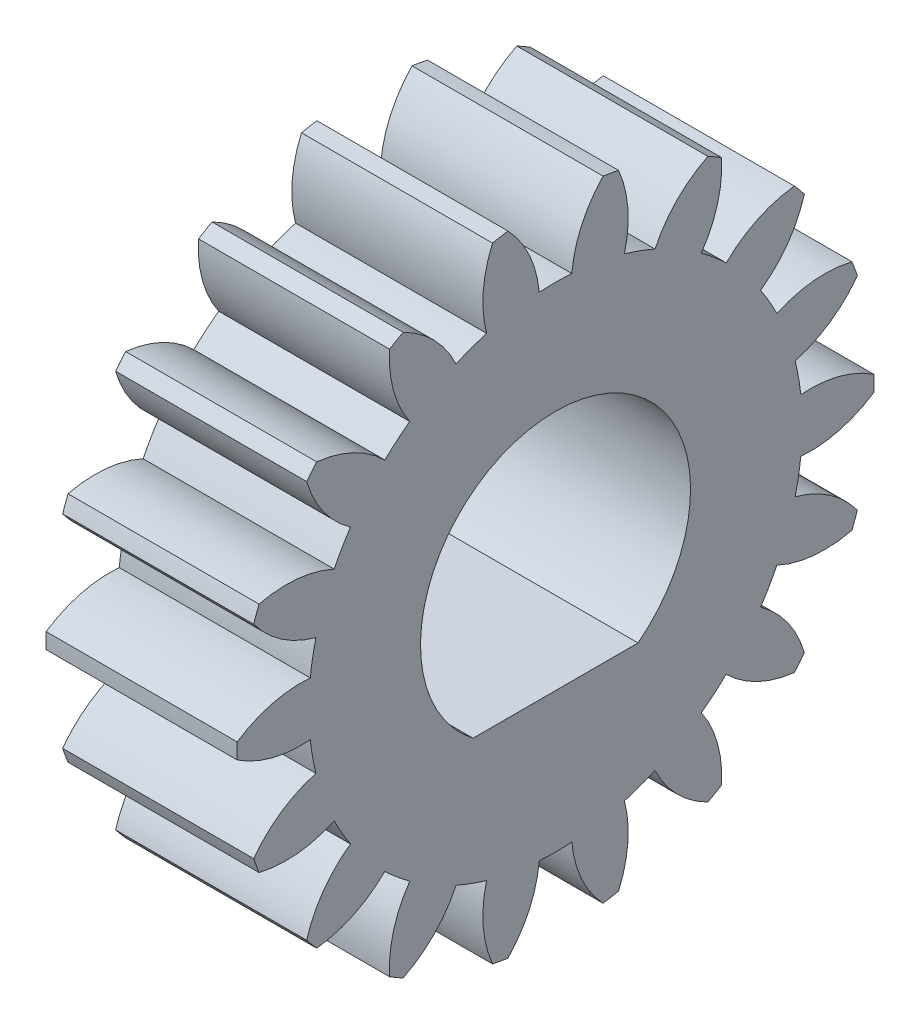
SolidWorks part; units mm, degrees
ref_plane "Plane1" through (0, 0, 0) normal (0, 0, 1) x (1, 0, 0)
ref_plane "Plane2" through (0, 0, 0) normal (0, 1, 0) x (1, 0, 0)
ref_plane "Plane3" through (0, 0, 0) normal (1, 0, 0) x (0, 0, -1)
sketch "HoldingSke" plane through (0, 0, 0) normal (0, 1, 0) x (1, 0, 0)
  line L0 (0, 0) -> (1.9021, -0.618)
  line L1 (-15, 0) -> (100, 0) construction
  line L2 (0, 0) -> (-2.1039, 2.3779)
  line L3 (0, 0) -> (-11.863, 4.5341)
  line L4 (0, 0) -> (8.2133, 2.6687)
  line L5 (0, 0) -> (-46.8476, -17.4728)
  line L6 (0, 0) -> (-3.3159, -2.2372)
  line L7 (-2.1039, 2.3779) -> (8.6586, 51.2059)
  line L8 (-76.2, 54.61) -> (-76.1, 54.61)
  line L9 (-71.009, 38.7566) -> (-53.1078, 45.2721)
  line L10 (-76.2, 71.12) -> (104.1128, 71.12)
  line L11 (0, 0) -> (-4, 0)
  line L12 (-76.2, 101.6) -> (-76.181, 101.6)
  line L13 (24.9733, 27.94) -> (52.9518, 28.4284)
  line L14 (24.9733, 27.94) -> (24.9743, 27.94)
  line L15 (24.9733, 27.94) -> (100.4006, 29.5858)
  line L16 (-63.627, -0.5) -> (-12.827, -0.5)
  circle A0 centre (0, 0) radius 0.5
  circle A1 centre (0, 0) radius 3.874
  circle A2 centre (0, 0) radius 37.5
  circle A3 centre (0, 0) radius 0.5
  dimension "MHD" = 7.748
  dimension "Hub_dia" = 75
  dimension "Bore" = 1
  dimension "MBD" = 1
  dimension "Num_teeth" = 18
  dimension "Pitch" = 2
  dimension "Overall_len" = 50
  dimension "Show_teeth" = 18
  dimension "Thickness" = 4
  dimension "OAL" = 50.0001
  dimension "T_dim" = 0.1
  dimension "Ap" = 20
  dimension "H" = 19.05
  dimension "Pitch_radius" = 180.3128
  dimension "Width" = 4
  dimension "Backlash" = 0.019
  dimension "Addendum_fac" = 1
  dimension "Dedendum_fac" = 1.25
  dimension "Clearance_fac" = 0.25
  dimension "Dedendum_add" = 0.001
  dimension "Module" = 0.5
sketch "BasProSke" plane through (0, 0, 0) normal (0, 1, 0) x (1, 0, 0)
  line L0 (-10, 0) -> (60, 0) construction
  line L1 (0, 0) -> (0, 5)
  line L2 (0, 0) -> (4, 0)
  line L3 (4, 0) -> (4, 5)
  line L4 (4, 5) -> (0, 5)
  dimension "Thickness" = 4
  dimension "Diameter" = 10
revolve "Base-Revolve" add sketch "BasProSke" angle 360 about L0
sketch "TooCutSke" plane through (0, 0, 0) normal (1, 0, 0) x (0, 0, -1)
  line L1 (0, 0) -> (0, 107) construction
  line L2 (0, 0) -> (-0.4254, 4.4798) construction
  line L3 (0, 0) -> (-1.5579, 8.835) construction
  line L4 (-0.4254, 4.4798) -> (-0.7789, 4.4175) construction
  arc A0 (0.2553, 3.8656) -> (-0.2553, 3.8656) centre (0, 0) ccw
  arc A1 (0.7686, 4.9663) -> (-0.7686, 4.9663) centre (0, 0) ccw
  circle A2 centre (0, 0) radius 4.5 construction
  circle A3 centre (0, 0) radius 4.2286 construction
  arc A4 (-0.2553, 3.8656) -> (-0.7686, 4.9663) centre (-2.0476, 3.6998) ccw
  arc A5 (0.7686, 4.9663) -> (0.2553, 3.8656) centre (2.0476, 3.6998) ccw
  dimension "Root_dia" = 7.748
  dimension "Overcut_dia" = 10.0508
  dimension "Pitch_dia" = 9
  dimension "Base_dia" = 8.4572
  dimension "Flank_rad" = 1.8
  dimension "Half_ang" = 10
  dimension "Half_CT" = 0.359
extrude "ToothCut" cut sketch "TooCutSke" along normal through all
fillet "Breaks" [suppressed] radius 0.01
fillet "RootFillets" [suppressed] radius 0.126
pattern_circular "TeethCuts" count 18 every 20 about axis through (-10, 0, 0) along (1, 0, 0) of "ToothCut", "RootFillets", "Breaks"
sketch "HubNeaOneSke" plane through (0, 0, 0) normal (-1, 0, 0) x (0, 0, 1)
  circle A0 centre (0, 0) radius 3.874
  dimension "Diameter" = 7.748
extrude "HubNearOne" [suppressed] add sketch "HubNeaOneSke" along normal blind 46.0001
sketch "HubNeaBotSke" plane through (0, 0, 0) normal (-1, 0, 0) x (0, 0, 1)
  circle A0 centre (0, 0) radius 3.874
  dimension "Diameter" = 7.748
extrude "HubNearBoth" [suppressed] add sketch "HubNeaBotSke" along normal blind 23
ref_plane "FarPln" through (4, 0, 0) normal (1, 0, 0) x (0, 0, -1)
sketch "HubFarSke" plane through (4, 0, 0) normal (1, 0, 0) x (0, 0, -1)
  circle A0 centre (0, 0) radius 3.874
  dimension "Diameter" = 7.748
extrude "HubFar" [suppressed] add sketch "HubFarSke" along normal blind 23
sketch "BorSke" plane through (0, 0, 0) normal (1, 0, 0) x (0, 0, -1)
  line L0 (-1.2954, -1.6782) -> (1.2954, -1.6782)
  line L2 (0, 0) -> (0, -1.6782)
  arc A0 (-1.2954, -1.6782) -> (1.2954, -1.6782) centre (0, 0) cw
extrude "Bore" cut sketch "BorSke" along normal mid plane 100.0001
sketch "KeySke" plane through (0, 0, 0) normal (1, 0, 0) x (0, 0, -1)
  line L0 (-0.05, 0) -> (-0.05, 0.6)
  line L1 (-0.05, 0.6) -> (0.05, 0.6)
  line L2 (0.05, 0.6) -> (0.05, 0)
  line L3 (0, 0) -> (0, 34) construction
  line L4 (-0.05, 0) -> (0.05, 0)
  dimension "Offset" = 0.6
  dimension "Width" = 0.1
extrude "Keyway" [suppressed] cut sketch "KeySke" along normal mid plane 100.0001
pattern_circular "Keyway2" [suppressed] count 2 every 90 about axis through (-10, 0, 0) along (1, 0, 0)
sketch "Sketch1" plane through (0, 0, 0) normal (-1, 0, 0) x (0, 0, 1)
  arc A72 (3.2201, 2.1539) -> (3.9082, 3.1187) centre (2.1803, 3.6232) ccw
  arc A73 (3.9082, 3.1187) -> (3.75, 3.3072) centre (0, 0) ccw
  arc A74 (3.75, 3.3072) -> (2.6803, 2.7971) centre (3.9467, 1.518) ccw
  arc A75 (2.6803, 2.7971) -> (2.2892, 3.1253) centre (0, 0) ccw
  arc A76 (2.2892, 3.1253) -> (2.6058, 4.2673) centre (0.8096, 4.1504) ccw
  arc A77 (2.6058, 4.2673) -> (2.3927, 4.3903) centre (0, 0) ccw
  arc A78 (2.3927, 4.3903) -> (1.562, 3.5451) centre (3.1895, 2.7763) ccw
  arc A79 (1.562, 3.5451) -> (1.0822, 3.7198) centre (0, 0) ccw
  arc A80 (1.0822, 3.7198) -> (0.9892, 4.9012) centre (-0.6587, 4.177) ccw
  arc A81 (0.9892, 4.9012) -> (0.7468, 4.9439) centre (0, 0) ccw
  arc A82 (0.7468, 4.9439) -> (0.2553, 3.8656) centre (2.0476, 3.6998) ccw
  arc A83 (0.2553, 3.8656) -> (-0.2553, 3.8656) centre (0, 0) ccw
  arc A84 (-0.2553, 3.8656) -> (-0.7468, 4.9439) centre (-2.0476, 3.6998) ccw
  arc A85 (-0.7468, 4.9439) -> (-0.9892, 4.9012) centre (0, 0) ccw
  arc A86 (-0.9892, 4.9012) -> (-1.0822, 3.7198) centre (0.6587, 4.177) ccw
  arc A87 (-1.0822, 3.7198) -> (-1.562, 3.5451) centre (0, 0) ccw
  arc A88 (-1.562, 3.5451) -> (-2.3927, 4.3903) centre (-3.1895, 2.7763) ccw
  arc A89 (-2.3927, 4.3903) -> (-2.6058, 4.2673) centre (0, 0) ccw
  arc A90 (-2.6058, 4.2673) -> (-2.2892, 3.1253) centre (-0.8096, 4.1504) ccw
  arc A91 (-2.2892, 3.1253) -> (-2.6803, 2.7971) centre (0, 0) ccw
  arc A92 (-2.6803, 2.7971) -> (-3.75, 3.3072) centre (-3.9467, 1.518) ccw
  arc A93 (-3.75, 3.3072) -> (-3.9082, 3.1187) centre (0, 0) ccw
  arc A94 (-3.9082, 3.1187) -> (-3.2201, 2.1539) centre (-2.1803, 3.6232) ccw
  arc A95 (-3.2201, 2.1539) -> (-3.4753, 1.7117) centre (0, 0) ccw
  arc A96 (-3.4753, 1.7117) -> (-4.655, 1.8252) centre (-4.2279, 0.0766) ccw
  arc A97 (-4.655, 1.8252) -> (-4.7391, 1.594) centre (0, 0) ccw
  arc A98 (-4.7391, 1.594) -> (-3.7625, 0.9226) centre (-3.288, 2.659) ccw
  arc A99 (-3.7625, 0.9226) -> (-3.8512, 0.4199) centre (0, 0) ccw
  arc A100 (-3.8512, 0.4199) -> (-4.9985, 0.1231) centre (-3.9991, -1.3741) ccw
  arc A101 (-4.9985, 0.1231) -> (-4.9985, -0.1231) centre (0, 0) ccw
  arc A102 (-4.9985, -0.1231) -> (-3.8512, -0.4199) centre (-3.9991, 1.3741) ccw
  arc A103 (-3.8512, -0.4199) -> (-3.7625, -0.9226) centre (0, 0) ccw
  arc A104 (-3.7625, -0.9226) -> (-4.7391, -1.594) centre (-3.288, -2.659) ccw
  arc A105 (-4.7391, -1.594) -> (-4.655, -1.8252) centre (0, 0) ccw
  arc A106 (-4.655, -1.8252) -> (-3.4753, -1.7117) centre (-4.2279, -0.0766) ccw
  arc A107 (-3.4753, -1.7117) -> (-3.2201, -2.1539) centre (0, 0) ccw
  arc A108 (-3.2201, -2.1539) -> (-3.9082, -3.1187) centre (-2.1803, -3.6232) ccw
  arc A109 (-3.9082, -3.1187) -> (-3.75, -3.3072) centre (0, 0) ccw
  arc A110 (-3.75, -3.3072) -> (-2.6803, -2.7971) centre (-3.9467, -1.518) ccw
  arc A111 (-2.6803, -2.7971) -> (-2.2892, -3.1253) centre (0, 0) ccw
  arc A112 (-2.2892, -3.1253) -> (-2.6058, -4.2673) centre (-0.8096, -4.1504) ccw
  arc A113 (-2.6058, -4.2673) -> (-2.3927, -4.3903) centre (0, 0) ccw
  arc A114 (-2.3927, -4.3903) -> (-1.562, -3.5451) centre (-3.1895, -2.7763) ccw
  arc A115 (-1.562, -3.5451) -> (-1.0822, -3.7198) centre (0, 0) ccw
  arc A116 (-1.0822, -3.7198) -> (-0.9892, -4.9012) centre (0.6587, -4.177) ccw
  arc A117 (-0.9892, -4.9012) -> (-0.7468, -4.9439) centre (0, 0) ccw
  arc A118 (-0.7468, -4.9439) -> (-0.2553, -3.8656) centre (-2.0476, -3.6998) ccw
  arc A119 (-0.2553, -3.8656) -> (0.2553, -3.8656) centre (0, 0) ccw
  arc A120 (0.2553, -3.8656) -> (0.7468, -4.9439) centre (2.0476, -3.6998) ccw
  arc A121 (0.7468, -4.9439) -> (0.9892, -4.9012) centre (0, 0) ccw
  arc A122 (0.9892, -4.9012) -> (1.0822, -3.7198) centre (-0.6587, -4.177) ccw
  arc A123 (1.0822, -3.7198) -> (1.562, -3.5451) centre (0, 0) ccw
  arc A124 (1.562, -3.5451) -> (2.3927, -4.3903) centre (3.1895, -2.7763) ccw
  arc A125 (2.3927, -4.3903) -> (2.6058, -4.2673) centre (0, 0) ccw
  arc A126 (2.6058, -4.2673) -> (2.2892, -3.1253) centre (0.8096, -4.1504) ccw
  arc A127 (2.2892, -3.1253) -> (2.6803, -2.7971) centre (0, 0) ccw
  arc A128 (2.6803, -2.7971) -> (3.75, -3.3072) centre (3.9467, -1.518) ccw
  arc A129 (3.75, -3.3072) -> (3.9082, -3.1187) centre (0, 0) ccw
  arc A130 (3.9082, -3.1187) -> (3.2201, -2.1539) centre (2.1803, -3.6232) ccw
  arc A131 (3.2201, -2.1539) -> (3.4753, -1.7117) centre (0, 0) ccw
  arc A132 (3.4753, -1.7117) -> (4.655, -1.8252) centre (4.2279, -0.0766) ccw
  arc A133 (4.655, -1.8252) -> (4.7391, -1.594) centre (0, 0) ccw
  arc A134 (4.7391, -1.594) -> (3.7625, -0.9226) centre (3.288, -2.659) ccw
  arc A135 (3.7625, -0.9226) -> (3.8512, -0.4199) centre (0, 0) ccw
  arc A136 (3.8512, -0.4199) -> (4.9985, -0.1231) centre (3.9991, 1.3741) ccw
  arc A137 (4.9985, -0.1231) -> (4.9985, 0.1231) centre (0, 0) ccw
  arc A138 (4.9985, 0.1231) -> (3.8512, 0.4199) centre (3.9991, -1.3741) ccw
  arc A139 (3.8512, 0.4199) -> (3.7625, 0.9226) centre (0, 0) ccw
  arc A140 (3.7625, 0.9226) -> (4.7391, 1.594) centre (3.288, 2.659) ccw
  arc A141 (4.7391, 1.594) -> (4.655, 1.8252) centre (0, 0) ccw
  arc A142 (4.655, 1.8252) -> (3.4753, 1.7117) centre (4.2279, 0.0766) ccw
  arc A143 (3.4753, 1.7117) -> (3.2201, 2.1539) centre (0, 0) ccw
  arc A144 (3.2201, 2.1539) -> (3.9082, 3.1187) centre (2.1803, 3.6232) ccw
  arc A145 (3.9082, 3.1187) -> (3.75, 3.3072) centre (0, 0) ccw
  arc A146 (3.75, 3.3072) -> (2.6803, 2.7971) centre (3.9467, 1.518) ccw
  arc A147 (2.6803, 2.7971) -> (2.2892, 3.1253) centre (0, 0) ccw
  arc A148 (2.2892, 3.1253) -> (2.6058, 4.2673) centre (0.8096, 4.1504) ccw
  arc A149 (2.6058, 4.2673) -> (2.3927, 4.3903) centre (0, 0) ccw
  arc A150 (2.3927, 4.3903) -> (1.562, 3.5451) centre (3.1895, 2.7763) ccw
  arc A151 (1.562, 3.5451) -> (1.0822, 3.7198) centre (0, 0) ccw
  arc A152 (1.0822, 3.7198) -> (0.9892, 4.9012) centre (-0.6587, 4.177) ccw
  arc A153 (0.9892, 4.9012) -> (0.7468, 4.9439) centre (0, 0) ccw
  arc A154 (0.7468, 4.9439) -> (0.2553, 3.8656) centre (2.0476, 3.6998) ccw
  arc A155 (0.2553, 3.8656) -> (-0.2553, 3.8656) centre (0, 0) ccw
  arc A156 (-0.2553, 3.8656) -> (-0.7468, 4.9439) centre (-2.0476, 3.6998) ccw
  arc A157 (-0.7468, 4.9439) -> (-0.9892, 4.9012) centre (0, 0) ccw
  arc A158 (-0.9892, 4.9012) -> (-1.0822, 3.7198) centre (0.6587, 4.177) ccw
  arc A159 (-1.0822, 3.7198) -> (-1.562, 3.5451) centre (0, 0) ccw
  arc A160 (-1.562, 3.5451) -> (-2.3927, 4.3903) centre (-3.1895, 2.7763) ccw
  arc A161 (-2.3927, 4.3903) -> (-2.6058, 4.2673) centre (0, 0) ccw
  arc A162 (-2.6058, 4.2673) -> (-2.2892, 3.1253) centre (-0.8096, 4.1504) ccw
  arc A163 (-2.2892, 3.1253) -> (-2.6803, 2.7971) centre (0, 0) ccw
  arc A164 (-2.6803, 2.7971) -> (-3.75, 3.3072) centre (-3.9467, 1.518) ccw
  arc A165 (-3.75, 3.3072) -> (-3.9082, 3.1187) centre (0, 0) ccw
  arc A166 (-3.9082, 3.1187) -> (-3.2201, 2.1539) centre (-2.1803, 3.6232) ccw
  arc A167 (-3.2201, 2.1539) -> (-3.4753, 1.7117) centre (0, 0) ccw
  arc A168 (-3.4753, 1.7117) -> (-4.655, 1.8252) centre (-4.2279, 0.0766) ccw
  arc A169 (-4.655, 1.8252) -> (-4.7391, 1.594) centre (0, 0) ccw
  arc A170 (-4.7391, 1.594) -> (-3.7625, 0.9226) centre (-3.288, 2.659) ccw
  arc A171 (-3.7625, 0.9226) -> (-3.8512, 0.4199) centre (0, 0) ccw
  arc A172 (-3.8512, 0.4199) -> (-4.9985, 0.1231) centre (-3.9991, -1.3741) ccw
  arc A173 (-4.9985, 0.1231) -> (-4.9985, -0.1231) centre (0, 0) ccw
  arc A174 (-4.9985, -0.1231) -> (-3.8512, -0.4199) centre (-3.9991, 1.3741) ccw
  arc A175 (-3.8512, -0.4199) -> (-3.7625, -0.9226) centre (0, 0) ccw
  arc A176 (-3.7625, -0.9226) -> (-4.7391, -1.594) centre (-3.288, -2.659) ccw
  arc A177 (-4.7391, -1.594) -> (-4.655, -1.8252) centre (0, 0) ccw
  arc A178 (-4.655, -1.8252) -> (-3.4753, -1.7117) centre (-4.2279, -0.0766) ccw
  arc A179 (-3.4753, -1.7117) -> (-3.2201, -2.1539) centre (0, 0) ccw
  arc A180 (-3.2201, -2.1539) -> (-3.9082, -3.1187) centre (-2.1803, -3.6232) ccw
  arc A181 (-3.9082, -3.1187) -> (-3.75, -3.3072) centre (0, 0) ccw
  arc A182 (-3.75, -3.3072) -> (-2.6803, -2.7971) centre (-3.9467, -1.518) ccw
  arc A183 (-2.6803, -2.7971) -> (-2.2892, -3.1253) centre (0, 0) ccw
  arc A184 (-2.2892, -3.1253) -> (-2.6058, -4.2673) centre (-0.8096, -4.1504) ccw
  arc A185 (-2.6058, -4.2673) -> (-2.3927, -4.3903) centre (0, 0) ccw
  arc A186 (-2.3927, -4.3903) -> (-1.562, -3.5451) centre (-3.1895, -2.7763) ccw
  arc A187 (-1.562, -3.5451) -> (-1.0822, -3.7198) centre (0, 0) ccw
  arc A188 (-1.0822, -3.7198) -> (-0.9892, -4.9012) centre (0.6587, -4.177) ccw
  arc A189 (-0.9892, -4.9012) -> (-0.7468, -4.9439) centre (0, 0) ccw
  arc A190 (-0.7468, -4.9439) -> (-0.2553, -3.8656) centre (-2.0476, -3.6998) ccw
  arc A191 (-0.2553, -3.8656) -> (0.2553, -3.8656) centre (0, 0) ccw
  arc A192 (0.2553, -3.8656) -> (0.7468, -4.9439) centre (2.0476, -3.6998) ccw
  arc A193 (0.7468, -4.9439) -> (0.9892, -4.9012) centre (0, 0) ccw
  arc A194 (0.9892, -4.9012) -> (1.0822, -3.7198) centre (-0.6587, -4.177) ccw
  arc A195 (1.0822, -3.7198) -> (1.562, -3.5451) centre (0, 0) ccw
  arc A196 (1.562, -3.5451) -> (2.3927, -4.3903) centre (3.1895, -2.7763) ccw
  arc A197 (2.3927, -4.3903) -> (2.6058, -4.2673) centre (0, 0) ccw
  arc A198 (2.6058, -4.2673) -> (2.2892, -3.1253) centre (0.8096, -4.1504) ccw
  arc A199 (2.2892, -3.1253) -> (2.6803, -2.7971) centre (0, 0) ccw
  arc A200 (2.6803, -2.7971) -> (3.75, -3.3072) centre (3.9467, -1.518) ccw
  arc A201 (3.75, -3.3072) -> (3.9082, -3.1187) centre (0, 0) ccw
  arc A202 (3.9082, -3.1187) -> (3.2201, -2.1539) centre (2.1803, -3.6232) ccw
  arc A203 (3.2201, -2.1539) -> (3.4753, -1.7117) centre (0, 0) ccw
  arc A204 (3.4753, -1.7117) -> (4.655, -1.8252) centre (4.2279, -0.0766) ccw
  arc A205 (4.655, -1.8252) -> (4.7391, -1.594) centre (0, 0) ccw
  arc A206 (4.7391, -1.594) -> (3.7625, -0.9226) centre (3.288, -2.659) ccw
  arc A207 (3.7625, -0.9226) -> (3.8512, -0.4199) centre (0, 0) ccw
  arc A208 (3.8512, -0.4199) -> (4.9985, -0.1231) centre (3.9991, 1.3741) ccw
  arc A209 (4.9985, -0.1231) -> (4.9985, 0.1231) centre (0, 0) ccw
  arc A210 (4.9985, 0.1231) -> (3.8512, 0.4199) centre (3.9991, -1.3741) ccw
  arc A211 (3.8512, 0.4199) -> (3.7625, 0.9226) centre (0, 0) ccw
  arc A212 (3.7625, 0.9226) -> (4.7391, 1.594) centre (3.288, 2.659) ccw
  arc A213 (4.7391, 1.594) -> (4.655, 1.8252) centre (0, 0) ccw
  arc A214 (4.655, 1.8252) -> (3.4753, 1.7117) centre (4.2279, 0.0766) ccw
  arc A215 (3.4753, 1.7117) -> (3.2201, 2.1539) centre (0, 0) ccw
  dimension "D1" = 0
extrude "Cut-Extrude1" cut sketch "Sketch1" against normal blind 1
equation "' \"Module@HoldingSke\" = 6.35"
equation "' \"Num_teeth@HoldingSke\" = 12"
equation "' \"Ap@HoldingSke\" =  20"
equation "' \"Ap@HoldingSke\" = 20"
equation "' \"Width@HoldingSke\" = 0.5 * 25.4"
equation "' \"Hub_dia@HoldingSke\"= 1 * 25.4"
equation "' \"Hub_dia@HoldingSke\" = 1 * 25.4"
equation "' \"Overall_len@HoldingSke\" = 1.0 * 25.4"
equation "' \"Bore@HoldingSke\" = 0.75 * 25.4"
equation "' \"T_dim@HoldingSke\" = 0.1 * 25.4"
equation "' \"Width@KeySke\" = 0.25 * 25.4"
equation "' \"Show_teeth@HoldingSke\" = 13"
equation "' \"Backlash@HoldingSke\" = 0.009 * 25.4"
equation "' \"Addendum_fac@HoldingSke\" = 1.0"
equation "' \"Dedendum_fac@HoldingSke\" = 1.25"
equation "' \"Dedendum_add@HoldingSke\" = 0.00005 * 25.4"
equation "' \"Clearance_fac@HoldingSke\" = 0.25"
equation "\"Pitch@HoldingSke\" = 1 / \"Module@HoldingSke\""
equation "\"Overcut_dia@TooCutSke\" = (\"Num_teeth@HoldingSke\" + 2 * \"Addendum_fac@HoldingSke\") / \"Pitch@HoldingSke\" + 0.002 * 25.4"
equation "\"Pitch_dia@TooCutSke\" = \"Num_teeth@HoldingSke\" / \"Pitch@HoldingSke\""
equation "\"Base_dia@TooCutSke\" = \"Num_teeth@HoldingSke\" / \"Pitch@HoldingSke\" * cos((\"Ap@HoldingSke\"  * 3.14159265 / 180))"
equation "\"Root_dia@TooCutSke\" = (\"Num_teeth@HoldingSke\" + 2) / \"Pitch@HoldingSke\" - 2 * (\"Addendum_fac@HoldingSke\" + \"Dedendum_fac@HoldingSke\") / \"Pitch@HoldingSke\" - \"Dedendum_add@HoldingSke\" * 2"
equation "\"Half_ang@TooCutSke\" = 180 / \"Num_teeth@HoldingSke\""
equation "\"Half_CT@TooCutSke\" = \"Num_teeth@HoldingSke\" / \"Pitch@HoldingSke\" * sin((3.14159265 / 2 / \"Num_teeth@HoldingSke\")) / 2 - 7 * \"Backlash@HoldingSke\" / 4"
equation "\"Flank_rad@TooCutSke\" = \"Num_teeth@HoldingSke\" / \"Pitch@HoldingSke\" / 5"
equation "\"Radius@RootFillets\" = \"Clearance_fac@HoldingSke\" / \"Pitch@HoldingSke\" + \"Dedendum_add@HoldingSke\""
equation "\"Break_rad@Breaks\" = 0.02 / \"Pitch@HoldingSke\""
equation "\"Thickness@HoldingSke\" = \"Width@HoldingSke\""
equation "\"OAL@HoldingSke\" = \"Thickness@HoldingSke\""
equation "\"MHD@HoldingSke\" = (\"Num_teeth@HoldingSke\" + 2) / \"Pitch@HoldingSke\" - 2 * (\"Addendum_fac@HoldingSke\" + \"Dedendum_fac@HoldingSke\")  / \"Pitch@HoldingSke\" - \"Dedendum_add@HoldingSke\" * 2"
equation "\"MBD@HoldingSke\" = (\"Num_teeth@HoldingSke\" + 2) / \"Pitch@HoldingSke\" - 2 * (\"Addendum_fac@HoldingSke\" + \"Dedendum_fac@HoldingSke\")  / \"Pitch@HoldingSke\" - \"Dedendum_add@HoldingSke\" * 2 - 0.002 * 25.4"
equation "\"MHD@HoldingSke\" = ((sgn( \"MHD@HoldingSke\" - \"Hub_dia@HoldingSke\" )-1)*( \"MHD@HoldingSke\" - \"Hub_dia@HoldingSke\" ))/-2+ \"Hub_dia@HoldingSke\""
equation "\"MBD@HoldingSke\" = ((sgn( \"MBD@HoldingSke\" - \"Bore@HoldingSke\" )-1)*( \"MBD@HoldingSke\" - \"Bore@HoldingSke\" ))/-2+ \"Bore@HoldingSke\""
equation "\"OAL@HoldingSke\" = ((sgn( \"OAL@HoldingSke\" - \"Overall_len@HoldingSke\" )+1)*( \"OAL@HoldingSke\" - \"Overall_len@HoldingSke\" ))/2 + \"Overall_len@HoldingSke\" + 0.000002 * 25.4"
equation "\"Num_teeth@TeethCuts\" = int( \"Show_teeth@HoldingSke\" ) + 1"
equation "\"Num_teeth@TeethCuts\" = ((sgn( \"Num_teeth@TeethCuts\" - \"Num_teeth@HoldingSke\" )-1)*( \"Num_teeth@TeethCuts\" - \"Num_teeth@HoldingSke\" ))/-2+ \"Num_teeth@HoldingSke\""
equation "\"Num_teeth@TeethCuts\" = ((sgn( \"Num_teeth@TeethCuts\" - 2.0)+1)*( \"Num_teeth@TeethCuts\" - 2.0))/2 +2.0"
equation "\"Angle@TeethCuts\" = 360.0 / \"Num_teeth@HoldingSke\""
equation "\"Diameter@BasProSke\" = (\"Num_teeth@HoldingSke\" + 2 * \"Addendum_fac@HoldingSke\") / \"Pitch@HoldingSke\""
equation "\"Thickness@BasProSke\"  = \"Thickness@HoldingSke\""
equation "' \"Fillet_rad@BasProSke\" =  \"Thickness@HoldingSke\" * 0.05"
equation "' \"Fillet_rad@BasProSke\" = \"Thickness@HoldingSke\" * 0.05"
equation "\"MHD@HoldingSke\" = ((sgn( \"MHD@HoldingSke\" - \"Root_dia@TooCutSke\" )-1)*( \"MHD@HoldingSke\" - \"Root_dia@TooCutSke\" ))/-2+ \"Root_dia@TooCutSke\""
equation "\"Diameter@HubNeaOneSke\" = \"MHD@HoldingSke\""
equation "\"Length@HubNearOne\" = \"OAL@HoldingSke\" - \"Thickness@BasProSke\""
equation "\"Diameter@HubNeaBotSke\" = \"MHD@HoldingSke\""
equation "\"Length@HubNearBoth\" = ( \"OAL@HoldingSke\" - \"Thickness@BasProSke\" ) / 2.0"
equation "\"Thickness@FarPln\" = \"Thickness@BasProSke\""
equation "\"Diameter@HubFarSke\" = \"MHD@HoldingSke\""
equation "\"Length@HubFar\" = ( \"OAL@HoldingSke\" - \"Thickness@BasProSke\" ) / 2.0"
equation "\"D1@Bore\" = \"OAL@HoldingSke\" * 2.0"
equation "\"D1@Keyway\" = \"OAL@HoldingSke\" * 2.0"
equation "\"Offset@KeySke\" = \"T_dim@HoldingSke\" + \"MBD@HoldingSke\" / 2.0"
